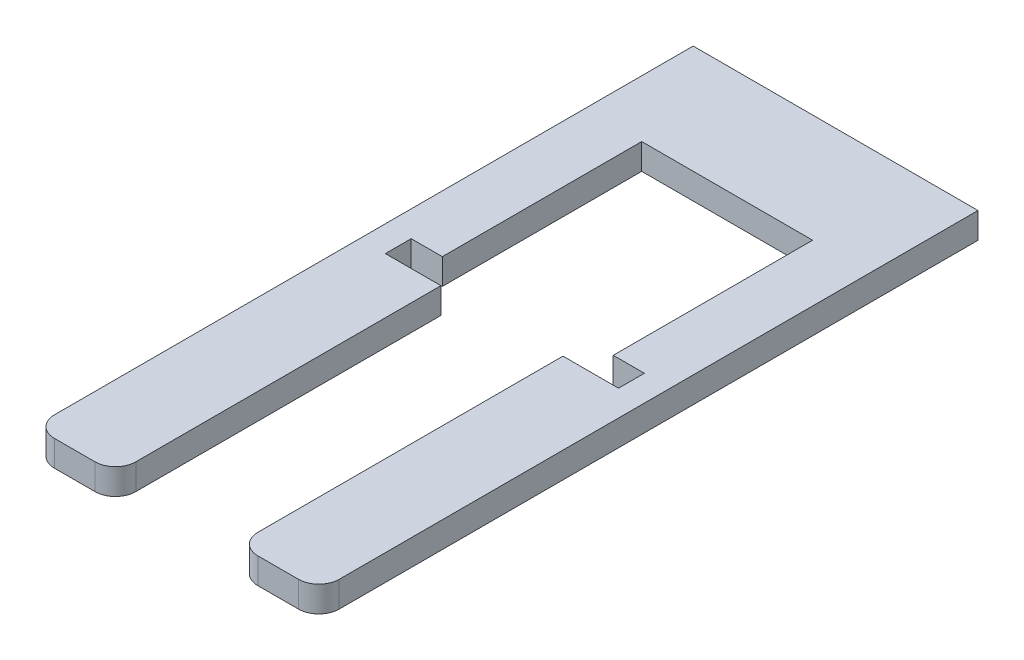
SolidWorks part; units mm, degrees
ref_plane "Front Plane" through (0, 0, 0) normal (0, 0, 1) x (1, 0, 0)
ref_plane "Top Plane" through (0, 0, 0) normal (0, 1, 0) x (1, 0, 0)
ref_plane "Right Plane" through (0, 0, 0) normal (1, 0, 0) x (0, 0, -1)
sketch "Sketch1" plane through (0, 0, 0) normal (0, 1, 0) x (1, 0, 0)
  line L0 (-35, 0) -> (-35, -200)
  line L1 (-35, -200) -> (35, -200)
  line L2 (35, -200) -> (35, 0)
  circle A0 centre (0, 0) radius 35
  point P3 (0, -200)
  dimension "D1" = 70
  dimension "D2" = 70
  dimension "D3" = 200
extrude "Boss-Extrude1" add sketch "Sketch1" along normal mid plane 6.35
sketch "Sketch2" plane through (0, 3.175, 0) normal (0, 1, 0) x (1, 0, 0)
  line L0 (35, -38) -> (-35, -38)
  line L1 (35, -200) -> (35, 0) construction
  line L2 (-35, 0) -> (-35, -200) construction
  line M1 (35, -200) -> (35, 0)
  arc M2 (35, 0) -> (-35, 0) centre (0, 0) ccw
  line M3 (-35, 0) -> (-35, -200)
  dimension "D1" = 38
extrude "Cut-Extrude1" cut sketch "Sketch2" against normal through all contours L0 M1 M2 M3
fillet "Fillet2" [suppressed] radius 8
sketch "Sketch3" plane through (0, 3.175, 0) normal (0, 1, 0) x (1, 0, 0)
  line L0 (-35, -200) -> (35, -200) construction
  line L1 (21, -120) -> (-21, -120)
  line L2 (21, -120) -> (21, -64.65)
  line L3 (21, -64.65) -> (-21, -64.65)
  line L4 (-21, -120) -> (-21, -64.65)
  line L5 (21, -120) -> (-21, -64.65) construction
  line L6 (21, -64.65) -> (-21, -120) construction
  line L7 (15, -200) -> (-15, -200)
  line L8 (15, -200) -> (15, -120)
  line L9 (15, -120) -> (-15, -120)
  line L10 (-15, -200) -> (-15, -120)
  line L11 (15, -200) -> (-15, -120) construction
  line L12 (15, -120) -> (-15, -200) construction
  line L15 (-21, -120) -> (-28.65, -120)
  line L16 (-21, -120) -> (-21, -113.65)
  line L17 (-21, -113.65) -> (-28.65, -113.65)
  line L18 (-28.65, -120) -> (-28.65, -113.65)
  line L19 (21, -120) -> (28.65, -120)
  line L20 (21, -120) -> (21, -113.65)
  line L21 (21, -113.65) -> (28.65, -113.65)
  line L22 (28.65, -120) -> (28.65, -113.65)
  point P0 (0, -92.325)
  point P5 (0, -160)
  point P14 (0, -200)
  line M12 (-35, -200) -> (35, -200)
  dimension "D1" = 80
  dimension "D2" = 30
  dimension "D3" = 55.35
  dimension "D4" = 42
  dimension "D5" = 6.35
  dimension "D6" = 7.65
extrude "Cut-Extrude2" cut sketch "Sketch3" against normal through all contours L4 L1 L2 L3 | L10 L8 L1 M12 | L18 L15 L4 L17 | L19 L22 L21 L2
fillet "Fillet3" radius 5 4 edges at (35, 0, 200) (-35, 0, 200) (15, 0, 200) (-15, 0, 200)
sketch "Sketch4" plane through (0, 3.175, 0) normal (0, 1, 0) x (1, 0, 0)
  circle A0 centre (15, -65.35) radius 2
  circle A1 centre (-15, -65.35) radius 2
  circle A2 centre (27.5, -195.35) radius 2
  circle A3 centre (-27.5, -195.35) radius 2
sketch "Sketch5" plane through (0, 3.175, 0) normal (0, 1, 0) x (1, 0, 0)
  line L1 (-35, -64.65) -> (-35, 20.35)
  line L2 (-35, -38) -> (-35, -195) construction
  arc A0 (-35, -64.65) -> (-35, 20.35) centre (-80, -22.15) ccw
  dimension "D2" = 45
  dimension "D1" = 85
